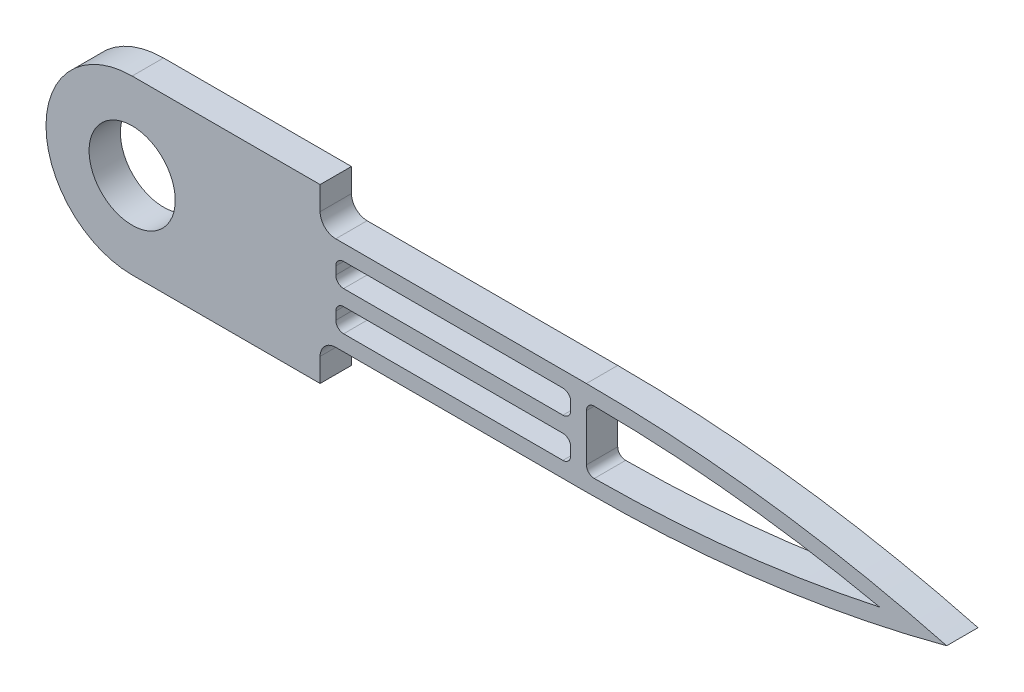
SolidWorks part; units mm, degrees
ref_plane "Front Plane" through (0, 0, 0) normal (0, 0, 1) x (1, 0, 0)
ref_plane "Top Plane" through (0, 0, 0) normal (0, 1, 0) x (1, 0, 0)
ref_plane "Right Plane" through (0, 0, 0) normal (1, 0, 0) x (0, 0, -1)
sketch "Sketch1" plane through (0, 0, 0) normal (0, 0, 1) x (1, 0, 0)
  line L0 (-20.4462, 0) -> (132.08, 0) construction
  line L1 (0, 13.97) -> (30.48, 13.97)
  line L3 (30.48, 13.97) -> (30.48, 7.62)
  line L4 (30.48, 7.62) -> (73.66, 7.62)
  line L7 (30.48, -7.62) -> (73.66, -7.62)
  line L8 (30.48, -13.97) -> (30.48, -7.62)
  line L9 (0, -13.97) -> (30.48, -13.97)
  arc A0 (0, 13.97) -> (0, -13.97) centre (0, 0) ccw
  arc A2 (73.66, 7.62) -> (132.08, 0) centre (73.66, -220.1333) cw
  arc A4 (73.66, -7.62) -> (132.08, 0) centre (73.66, 220.1333) ccw
  dimension "D2" = 13.97
  dimension "D6" = 7.62
  dimension "D1" = 30.48
  dimension "D3" = 6.35
  dimension "D4" = 101.6
  dimension "D5" = 43.18
extrude "Boss-Extrude1" add sketch "Sketch1" along normal blind 5.08
sketch "Sketch2" plane through (0, 0, 5.08) normal (0, 0, 1) x (1, 0, 0)
  circle A0 centre (0, 0) radius 6.985
  dimension "D1" = 13.97
extrude "Cut-Extrude1" cut sketch "Sketch2" against normal through all
fillet "Fillet1" radius 2.54 2 edges at (30.48, -7.62, 2.54) (30.48, 7.62, 2.54)
sketch "Sketch3" plane through (0, 0, 5.08) normal (0, 0, 1) x (1, 0, 0)
  line L20 (27.64, 0) -> (139.8385, 0) construction
  line L21 (33.02, -5.08) -> (33.02, -1.27)
  line L22 (33.02, -5.08) -> (73.66, -5.08)
  line L23 (73.66, 5.08) -> (33.02, 5.08)
  line L24 (33.02, -5.08) -> (71.12, -5.08)
  line L25 (71.12, 5.08) -> (33.02, 5.08)
  line L26 (33.02, -1.27) -> (71.12, -1.27)
  line L27 (71.12, -1.27) -> (71.12, -5.08)
  line L28 (73.66, -5.08) -> (73.66, 5.08)
  line L29 (71.12, 1.27) -> (71.12, 5.08)
  line L30 (33.02, 5.08) -> (33.02, 1.27)
  line L31 (33.02, 1.27) -> (71.12, 1.27)
  arc A14 (73.66, -5.08) -> (121.2243, 0) centre (73.66, 220.1333) ccw
  arc A15 (121.2243, 0) -> (73.66, 5.08) centre (73.66, -220.1333) ccw
  arc A16 (73.66, -5.08) -> (121.2243, 0) centre (73.66, 220.1333) ccw
  arc A17 (121.2243, 0) -> (73.66, 5.08) centre (73.66, -220.1333) ccw
  dimension "D1" = 2.54
  dimension "D2" = 1.27
  dimension "D3" = 2.54
extrude "Cut-Extrude2" cut sketch "Sketch3" against normal through all
fillet "Fillet2" radius 1.27 10 edges at (73.66, 5.08, 2.54) (73.66, -5.08, 2.54) (33.02, -5.08, 2.54) (71.12, -5.08, 2.54) (71.12, 5.08, 2.54) (71.12, 1.27, 2.54) (33.02, 5.08, 2.54) (33.02, 1.27, 2.54) (71.12, -1.27, 2.54) (33.02, -1.27, 2.54)
